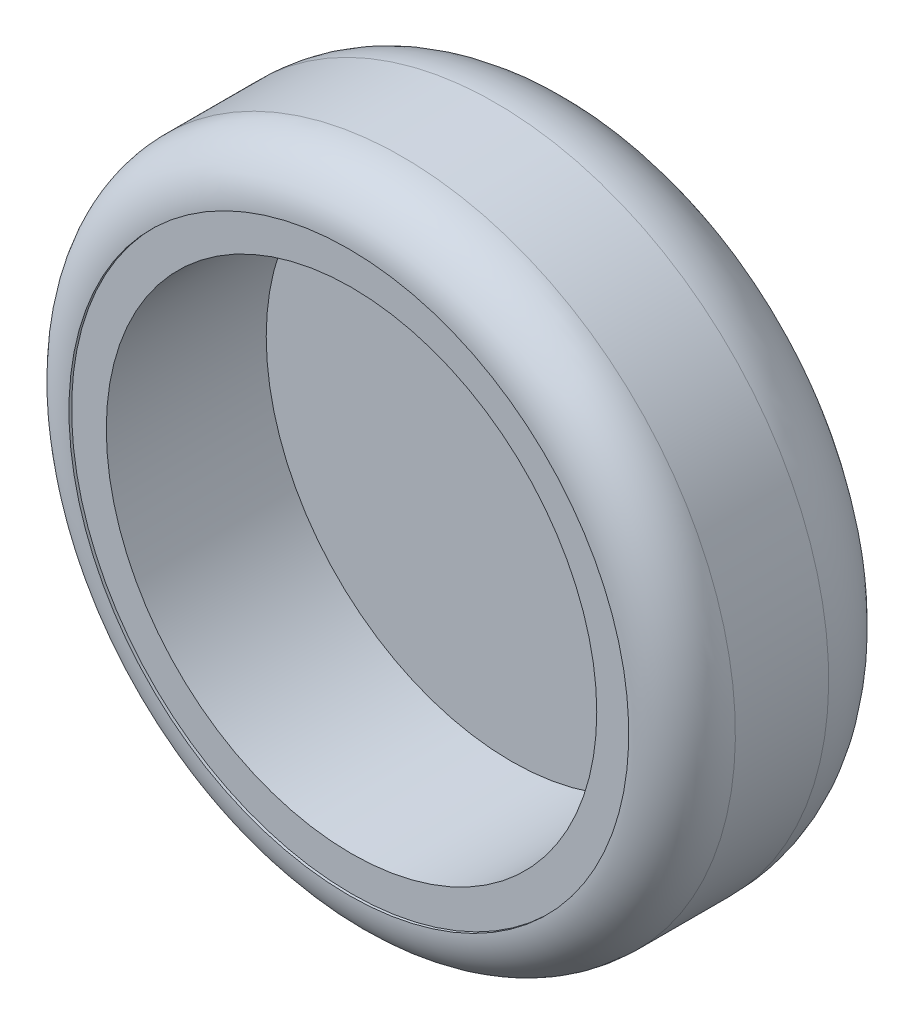
SolidWorks part; units mm, degrees
ref_plane "前视基准面" through (0, 0, 0) normal (0, 0, 1) x (1, 0, 0)
ref_plane "上视基准面" through (0, 0, 0) normal (0, 1, 0) x (1, 0, 0)
ref_plane "右视基准面" through (0, 0, 0) normal (1, 0, 0) x (0, 0, -1)
other "Configuration Table"
sketch "草图2" plane through (0, 0, 0) normal (1, 0, 0) x (0, 0, -1)
  line L5 (1.6, 0) -> (4.5, 0)
  line L6 (4.5, 0) -> (4.5, 9)
  line L7 (1, 12.5) -> (-2.5, 12.5)
  line L10 (1.6, 9.2) -> (1.6, 0)
  line L15 (-4.5, 10.5) -> (-4.4, 10.5)
  line L16 (-4.4, 9.2) -> (-4.4, 10.5)
  line L17 (-4.4, 9.2) -> (1.6, 9.2)
  arc A0 (-2.5, 12.5) -> (-4.5, 10.5) centre (-2.5, 10.5) ccw
  arc A2 (4.5, 9) -> (1, 12.5) centre (1, 9) ccw
  dimension "D1" = 2
  dimension "D2" = 3.5
revolve "旋转2" add sketch "草图2" angle 360 about L5
